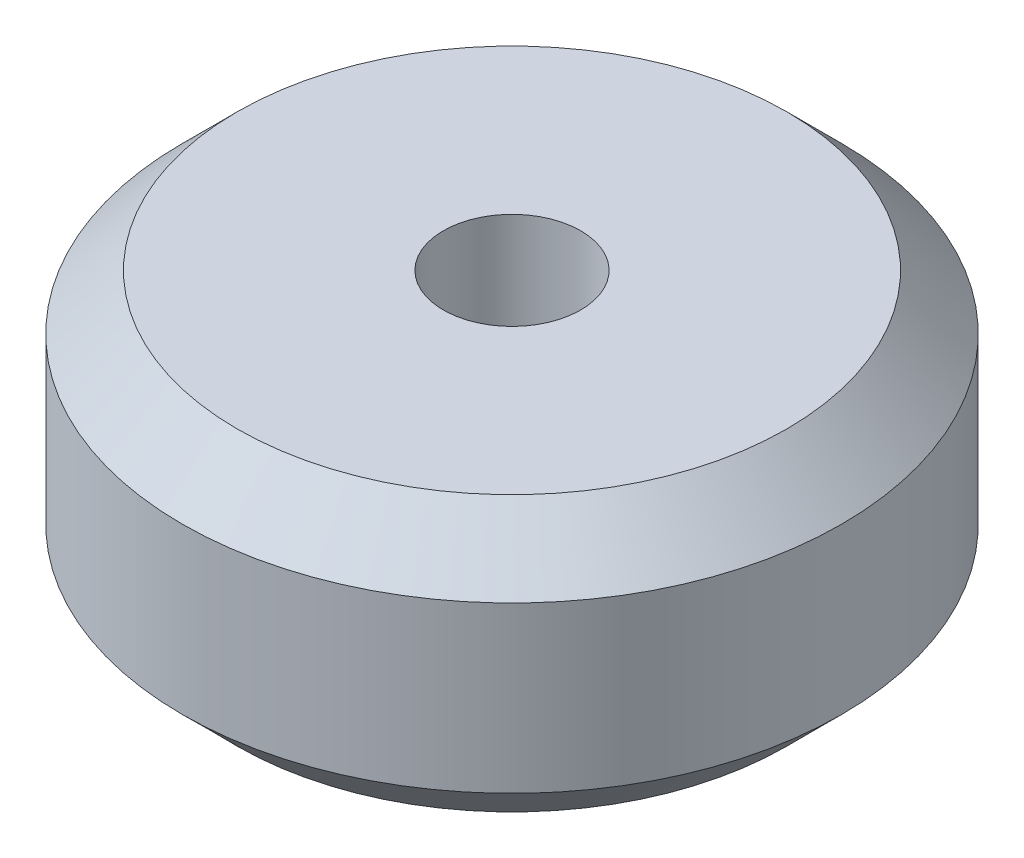
SolidWorks part; units mm, degrees
ref_plane "Front Plane" through (0, 0, 0) normal (0, 0, 1) x (1, 0, 0)
ref_plane "Top Plane" through (0, 0, 0) normal (0, 1, 0) x (1, 0, 0)
ref_plane "Right Plane" through (0, 0, 0) normal (1, 0, 0) x (0, 0, -1)
sketch "Sketch1" plane through (0, 0, 0) normal (1, 0, 0) x (0, 0, -1)
  line L0 (0, 0) -> (0, 10) construction
  line L1 (0, 10) -> (2.5, 10) construction
  line L2 (0, 0) -> (2.5, 0) construction
  line L3 (2.5, 10) -> (2.5, 0)
  line L4 (2.5, 10) -> (10, 10)
  line L5 (10, 10) -> (12, 8)
  line L6 (12, 8) -> (12, 2)
  line L7 (12, 2) -> (10, 0)
  line L8 (10, 0) -> (2.5, 0)
  dimension "D1" = 10
  dimension "D2" = 2.5
  dimension "D3" = 9.5
  dimension "D4" = 6
revolve "Revolve1" add sketch "Sketch1" angle 360 about L0
ref_plane "Plane1" through (0, 0, -12) normal (0, 0, -1) x (-1, 0, 0)
sketch "Sketch2" plane through (0, 0, -12) normal (0, 0, -1) x (-1, 0, 0)
  line L0 (0, 10) -> (0, 0) construction
  line L1 (2.5, 10) -> (-2.5, 10) construction
  line L2 (-10, 0) -> (10, 0) construction
  circle A0 centre (0, 5) radius 1.27 construction
  dimension "D1" = 2.54
